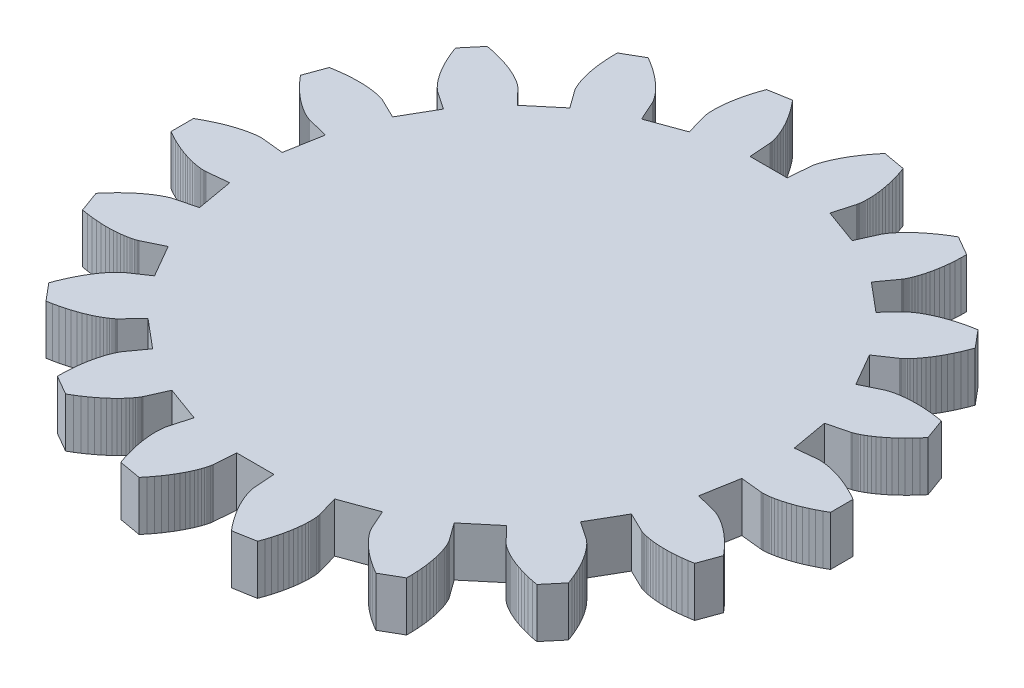
SolidWorks part; units mm, degrees
ref_plane "Front Plane" through (0, 0, 0) normal (0, 0, 1) x (1, 0, 0)
ref_plane "Top Plane" through (0, 0, 0) normal (0, 1, 0) x (1, 0, 0)
ref_plane "Right Plane" through (0, 0, 0) normal (1, 0, 0) x (0, 0, -1)
sketch "Sketch2" plane through (0, 0, 0) normal (0, 1, 0) x (1, 0, 0)
  line L0 (15.5186, 1.5911) -> (16.8263, 1.7252)
  line L1 (16.8263, 1.7252) -> (16.8356, 1.7259)
  line L2 (16.8356, 1.7259) -> (16.8635, 1.7273)
  line L3 (16.8635, 1.7273) -> (16.9101, 1.7282)
  line L4 (16.9101, 1.7282) -> (16.9754, 1.7272)
  line L5 (16.9754, 1.7272) -> (17.0592, 1.7232)
  line L6 (17.0592, 1.7232) -> (17.1615, 1.7149)
  line L7 (17.1615, 1.7149) -> (17.282, 1.7011)
  line L8 (17.282, 1.7011) -> (17.4203, 1.6805)
  line L9 (17.4203, 1.6805) -> (17.5763, 1.6521)
  line L10 (17.5763, 1.6521) -> (17.7495, 1.6145)
  line L11 (17.7495, 1.6145) -> (17.9394, 1.5667)
  line L12 (17.9394, 1.5667) -> (18.1456, 1.5074)
  line L13 (18.1456, 1.5074) -> (18.3674, 1.4356)
  line L14 (18.3674, 1.4356) -> (18.6042, 1.3501)
  line L15 (18.6042, 1.3501) -> (18.8555, 1.2499)
  line L16 (18.8555, 1.2499) -> (19.1203, 1.1339)
  line L17 (19.1203, 1.1339) -> (19.398, 1.0012)
  line L18 (19.398, 1.0012) -> (19.6876, 0.8507)
  line L19 (19.6876, 0.8507) -> (19.9884, 0.6815)
  line L20 (19.9884, 0.6815) -> (19.9884, -0.6815)
  line L21 (19.9884, -0.6815) -> (19.6876, -0.8507)
  line L22 (19.6876, -0.8507) -> (19.398, -1.0012)
  line L23 (19.398, -1.0012) -> (19.1203, -1.1339)
  line L24 (19.1203, -1.1339) -> (18.8555, -1.2499)
  line L25 (18.8555, -1.2499) -> (18.6042, -1.3501)
  line L26 (18.6042, -1.3501) -> (18.3674, -1.4356)
  line L27 (18.3674, -1.4356) -> (18.1456, -1.5074)
  line L28 (18.1456, -1.5074) -> (17.9394, -1.5667)
  line L29 (17.9394, -1.5667) -> (17.7495, -1.6145)
  line L30 (17.7495, -1.6145) -> (17.5763, -1.6521)
  line L31 (17.5763, -1.6521) -> (17.4203, -1.6805)
  line L32 (17.4203, -1.6805) -> (17.282, -1.7011)
  line L33 (17.282, -1.7011) -> (17.1615, -1.7149)
  line L34 (17.1615, -1.7149) -> (17.0592, -1.7232)
  line L35 (17.0592, -1.7232) -> (16.9754, -1.7272)
  line L36 (16.9754, -1.7272) -> (16.9101, -1.7282)
  line L37 (16.9101, -1.7282) -> (16.8635, -1.7273)
  line L38 (16.8635, -1.7273) -> (16.8356, -1.7259)
  line L39 (16.8356, -1.7259) -> (16.8263, -1.7252)
  line L40 (16.8263, -1.7252) -> (15.5186, -1.5911)
  line L41 (15.5186, -1.5911) -> (15.1269, -3.8126)
  line L42 (15.1269, -3.8126) -> (16.4016, -4.1338)
  line L43 (16.4016, -4.1338) -> (16.4105, -4.1363)
  line L44 (16.4105, -4.1363) -> (16.4373, -4.1445)
  line L45 (16.4373, -4.1445) -> (16.4814, -4.1597)
  line L46 (16.4814, -4.1597) -> (16.5424, -4.1829)
  line L47 (16.5424, -4.1829) -> (16.6198, -4.2154)
  line L48 (16.6198, -4.2154) -> (16.7131, -4.2581)
  line L49 (16.7131, -4.2581) -> (16.8215, -4.3123)
  line L50 (16.8215, -4.3123) -> (16.9445, -4.3789)
  line L51 (16.9445, -4.3789) -> (17.0814, -4.459)
  line L52 (17.0814, -4.459) -> (17.2313, -4.5535)
  line L53 (17.2313, -4.5535) -> (17.3934, -4.6634)
  line L54 (17.3934, -4.6634) -> (17.5668, -4.7896)
  line L55 (17.5668, -4.7896) -> (17.7507, -4.933)
  line L56 (17.7507, -4.933) -> (17.944, -5.0943)
  line L57 (17.944, -5.0943) -> (18.1458, -5.2744)
  line L58 (18.1458, -5.2744) -> (18.355, -5.474)
  line L59 (18.355, -5.474) -> (18.5705, -5.6937)
  line L60 (18.5705, -5.6937) -> (18.7913, -5.9342)
  line L61 (18.7913, -5.9342) -> (19.016, -6.196)
  line L62 (19.016, -6.196) -> (18.5499, -7.4769)
  line L63 (18.5499, -7.4769) -> (18.2094, -7.5329)
  line L64 (18.2094, -7.5329) -> (17.8857, -7.5753)
  line L65 (17.8857, -7.5753) -> (17.5794, -7.6051)
  line L66 (17.5794, -7.6051) -> (17.2908, -7.6235)
  line L67 (17.2908, -7.6235) -> (17.0205, -7.6317)
  line L68 (17.0205, -7.6317) -> (16.7687, -7.631)
  line L69 (16.7687, -7.631) -> (16.5357, -7.6226)
  line L70 (16.5357, -7.6226) -> (16.3217, -7.6078)
  line L71 (16.3217, -7.6078) -> (16.1269, -7.5878)
  line L72 (16.1269, -7.5878) -> (15.9513, -7.5639)
  line L73 (15.9513, -7.5639) -> (15.795, -7.5373)
  line L74 (15.795, -7.5373) -> (15.6579, -7.5093)
  line L75 (15.6579, -7.5093) -> (15.54, -7.481)
  line L76 (15.54, -7.481) -> (15.4411, -7.4539)
  line L77 (15.4411, -7.4539) -> (15.3609, -7.429)
  line L78 (15.3609, -7.429) -> (15.2993, -7.4075)
  line L79 (15.2993, -7.4075) -> (15.2557, -7.3908)
  line L80 (15.2557, -7.3908) -> (15.23, -7.3799)
  line L81 (15.23, -7.3799) -> (15.2215, -7.376)
  line L82 (15.2215, -7.376) -> (14.0386, -6.8028)
  line L83 (14.0386, -6.8028) -> (12.9107, -8.7563)
  line L84 (12.9107, -8.7563) -> (13.9986, -9.4942)
  line L85 (13.9986, -9.4942) -> (14.0062, -9.4996)
  line L86 (14.0062, -9.4996) -> (14.0285, -9.5164)
  line L87 (14.0285, -9.5164) -> (14.0647, -9.5458)
  line L88 (14.0647, -9.5458) -> (14.1141, -9.5885)
  line L89 (14.1141, -9.5885) -> (14.1758, -9.6454)
  line L90 (14.1758, -9.6454) -> (14.2488, -9.7175)
  line L91 (14.2488, -9.7175) -> (14.3322, -9.8055)
  line L92 (14.3322, -9.8055) -> (14.425, -9.9102)
  line L93 (14.425, -9.9102) -> (14.5262, -10.0323)
  line L94 (14.5262, -10.0323) -> (14.6347, -10.1723)
  line L95 (14.6347, -10.1723) -> (14.7494, -10.3311)
  line L96 (14.7494, -10.3311) -> (14.8692, -10.509)
  line L97 (14.8692, -10.509) -> (14.993, -10.7066)
  line L98 (14.993, -10.7066) -> (15.1195, -10.9243)
  line L99 (15.1195, -10.9243) -> (15.2475, -11.1626)
  line L100 (15.2475, -11.1626) -> (15.3759, -11.4217)
  line L101 (15.3759, -11.4217) -> (15.5032, -11.7018)
  line L102 (15.5032, -11.7018) -> (15.6284, -12.0033)
  line L103 (15.6284, -12.0033) -> (15.7501, -12.3262)
  line L104 (15.7501, -12.3262) -> (14.8739, -13.3704)
  line L105 (14.8739, -13.3704) -> (14.5348, -13.3066)
  line L106 (14.5348, -13.3066) -> (14.2162, -13.2357)
  line L107 (14.2162, -13.2357) -> (13.9181, -13.1589)
  line L108 (13.9181, -13.1589) -> (13.6407, -13.0775)
  line L109 (13.6407, -13.0775) -> (13.3838, -12.9928)
  line L110 (13.3838, -12.9928) -> (13.1475, -12.906)
  line L111 (13.1475, -12.906) -> (12.9314, -12.8185)
  line L112 (12.9314, -12.8185) -> (12.7353, -12.7314)
  line L113 (12.7353, -12.7314) -> (12.5591, -12.6459)
  line L114 (12.5591, -12.6459) -> (12.4023, -12.5634)
  line L115 (12.4023, -12.5634) -> (12.2645, -12.4849)
  line L116 (12.2645, -12.4849) -> (12.1453, -12.4117)
  line L117 (12.1453, -12.4117) -> (12.0442, -12.3449)
  line L118 (12.0442, -12.3449) -> (11.9605, -12.2855)
  line L119 (11.9605, -12.2855) -> (11.8937, -12.2347)
  line L120 (11.8937, -12.2347) -> (11.8431, -12.1935)
  line L121 (11.8431, -12.1935) -> (11.8079, -12.1629)
  line L122 (11.8079, -12.1629) -> (11.7874, -12.1438)
  line L123 (11.7874, -12.1438) -> (11.7808, -12.1373)
  line L124 (11.7808, -12.1373) -> (10.8652, -11.194)
  line L125 (10.8652, -11.194) -> (9.1373, -12.644)
  line L126 (9.1373, -12.644) -> (9.9072, -13.7094)
  line L127 (9.9072, -13.7094) -> (9.9125, -13.7171)
  line L128 (9.9125, -13.7171) -> (9.9277, -13.7406)
  line L129 (9.9277, -13.7406) -> (9.9517, -13.7805)
  line L130 (9.9517, -13.7805) -> (9.9835, -13.8375)
  line L131 (9.9835, -13.8375) -> (10.0219, -13.9122)
  line L132 (10.0219, -13.9122) -> (10.0659, -14.0049)
  line L133 (10.0659, -14.0049) -> (10.1141, -14.1161)
  line L134 (10.1141, -14.1161) -> (10.1656, -14.2462)
  line L135 (10.1656, -14.2462) -> (10.2189, -14.3955)
  line L136 (10.2189, -14.3955) -> (10.273, -14.5642)
  line L137 (10.273, -14.5642) -> (10.3265, -14.7526)
  line L138 (10.3265, -14.7526) -> (10.3782, -14.9608)
  line L139 (10.3782, -14.9608) -> (10.4269, -15.1888)
  line L140 (10.4269, -15.1888) -> (10.4713, -15.4367)
  line L141 (10.4713, -15.4367) -> (10.5102, -15.7044)
  line L142 (10.5102, -15.7044) -> (10.5421, -15.9917)
  line L143 (10.5421, -15.9917) -> (10.566, -16.2985)
  line L144 (10.566, -16.2985) -> (10.5805, -16.6246)
  line L145 (10.5805, -16.6246) -> (10.5844, -16.9697)
  line L146 (10.5844, -16.9697) -> (9.404, -17.6512)
  line L147 (9.404, -17.6512) -> (9.1071, -17.4753)
  line L148 (9.1071, -17.4753) -> (8.8319, -17.2997)
  line L149 (8.8319, -17.2997) -> (8.5781, -17.1256)
  line L150 (8.5781, -17.1256) -> (8.3453, -16.9542)
  line L151 (8.3453, -16.9542) -> (8.1329, -16.7868)
  line L152 (8.1329, -16.7868) -> (7.9404, -16.6244)
  line L153 (7.9404, -16.6244) -> (7.7673, -16.4682)
  line L154 (7.7673, -16.4682) -> (7.6129, -16.3193)
  line L155 (7.6129, -16.3193) -> (7.4765, -16.1788)
  line L156 (7.4765, -16.1788) -> (7.3574, -16.0476)
  line L157 (7.3574, -16.0476) -> (7.2548, -15.9267)
  line L158 (7.2548, -15.9267) -> (7.1678, -15.8171)
  line L159 (7.1678, -15.8171) -> (7.0956, -15.7197)
  line L160 (7.0956, -15.7197) -> (7.0373, -15.6353)
  line L161 (7.0373, -15.6353) -> (6.9919, -15.5647)
  line L162 (6.9919, -15.5647) -> (6.9584, -15.5087)
  line L163 (6.9584, -15.5087) -> (6.9358, -15.4679)
  line L164 (6.9358, -15.4679) -> (6.9231, -15.443)
  line L165 (6.9231, -15.443) -> (6.9191, -15.4345)
  line L166 (6.9191, -15.4345) -> (6.3814, -14.2351)
  line L167 (6.3814, -14.2351) -> (4.2617, -15.0066)
  line L168 (4.2617, -15.0066) -> (4.6208, -16.2711)
  line L169 (4.6208, -16.2711) -> (4.6231, -16.2801)
  line L170 (4.6231, -16.2801) -> (4.6294, -16.3074)
  line L171 (4.6294, -16.3074) -> (4.6383, -16.3531)
  line L172 (4.6383, -16.3531) -> (4.6487, -16.4176)
  line L173 (4.6487, -16.4176) -> (4.6593, -16.5008)
  line L174 (4.6593, -16.5008) -> (4.6689, -16.603)
  line L175 (4.6689, -16.603) -> (4.6762, -16.724)
  line L176 (4.6762, -16.724) -> (4.68, -16.8639)
  line L177 (4.68, -16.8639) -> (4.6791, -17.0224)
  line L178 (4.6791, -17.0224) -> (4.6722, -17.1995)
  line L179 (4.6722, -17.1995) -> (4.658, -17.3948)
  line L180 (4.658, -17.3948) -> (4.6354, -17.6081)
  line L181 (4.6354, -17.6081) -> (4.6032, -17.8391)
  line L182 (4.6032, -17.8391) -> (4.5602, -18.0872)
  line L183 (4.5602, -18.0872) -> (4.5051, -18.352)
  line L184 (4.5051, -18.352) -> (4.4369, -18.6329)
  line L185 (4.4369, -18.6329) -> (4.3544, -18.9294)
  line L186 (4.3544, -18.9294) -> (4.2565, -19.2408)
  line L187 (4.2565, -19.2408) -> (4.1421, -19.5664)
  line L188 (4.1421, -19.5664) -> (2.7998, -19.8031)
  line L189 (2.7998, -19.8031) -> (2.581, -19.5363)
  line L190 (2.581, -19.5363) -> (2.3825, -19.2771)
  line L191 (2.3825, -19.2771) -> (2.2035, -19.0267)
  line L192 (2.2035, -19.0267) -> (2.0433, -18.786)
  line L193 (2.0433, -18.786) -> (1.901, -18.556)
  line L194 (1.901, -18.556) -> (1.7757, -18.3376)
  line L195 (1.7757, -18.3376) -> (1.6664, -18.1316)
  line L196 (1.6664, -18.1316) -> (1.5723, -17.9389)
  line L197 (1.5723, -17.9389) -> (1.4922, -17.7602)
  line L198 (1.4922, -17.7602) -> (1.4251, -17.5962)
  line L199 (1.4251, -17.5962) -> (1.37, -17.4475)
  line L200 (1.37, -17.4475) -> (1.3258, -17.3148)
  line L201 (1.3258, -17.3148) -> (1.2912, -17.1986)
  line L202 (1.2912, -17.1986) -> (1.2653, -17.0993)
  line L203 (1.2653, -17.0993) -> (1.2468, -17.0174)
  line L204 (1.2468, -17.0174) -> (1.2345, -16.9533)
  line L205 (1.2345, -16.9533) -> (1.2272, -16.9073)
  line L206 (1.2272, -16.9073) -> (1.2238, -16.8795)
  line L207 (1.2238, -16.8795) -> (1.2229, -16.8702)
  line L208 (1.2229, -16.8702) -> (1.1279, -15.5592)
  line L209 (1.1279, -15.5592) -> (-1.1279, -15.5592)
  line L210 (-1.1279, -15.5592) -> (-1.2229, -16.8702)
  line L211 (-1.2229, -16.8702) -> (-1.2238, -16.8795)
  line L212 (-1.2238, -16.8795) -> (-1.2272, -16.9073)
  line L213 (-1.2272, -16.9073) -> (-1.2345, -16.9533)
  line L214 (-1.2345, -16.9533) -> (-1.2468, -17.0174)
  line L215 (-1.2468, -17.0174) -> (-1.2653, -17.0993)
  line L216 (-1.2653, -17.0993) -> (-1.2912, -17.1986)
  line L217 (-1.2912, -17.1986) -> (-1.3258, -17.3148)
  line L218 (-1.3258, -17.3148) -> (-1.37, -17.4475)
  line L219 (-1.37, -17.4475) -> (-1.4251, -17.5962)
  line L220 (-1.4251, -17.5962) -> (-1.4922, -17.7602)
  line L221 (-1.4922, -17.7602) -> (-1.5723, -17.9389)
  line L222 (-1.5723, -17.9389) -> (-1.6664, -18.1316)
  line L223 (-1.6664, -18.1316) -> (-1.7757, -18.3376)
  line L224 (-1.7757, -18.3376) -> (-1.901, -18.556)
  line L225 (-1.901, -18.556) -> (-2.0433, -18.786)
  line L226 (-2.0433, -18.786) -> (-2.2035, -19.0267)
  line L227 (-2.2035, -19.0267) -> (-2.3825, -19.2771)
  line L228 (-2.3825, -19.2771) -> (-2.581, -19.5363)
  line L229 (-2.581, -19.5363) -> (-2.7998, -19.8031)
  line L230 (-2.7998, -19.8031) -> (-4.1421, -19.5664)
  line L231 (-4.1421, -19.5664) -> (-4.2565, -19.2408)
  line L232 (-4.2565, -19.2408) -> (-4.3544, -18.9294)
  line L233 (-4.3544, -18.9294) -> (-4.4369, -18.6329)
  line L234 (-4.4369, -18.6329) -> (-4.5051, -18.352)
  line L235 (-4.5051, -18.352) -> (-4.5602, -18.0872)
  line L236 (-4.5602, -18.0872) -> (-4.6032, -17.8391)
  line L237 (-4.6032, -17.8391) -> (-4.6354, -17.6081)
  line L238 (-4.6354, -17.6081) -> (-4.658, -17.3948)
  line L239 (-4.658, -17.3948) -> (-4.6722, -17.1995)
  line L240 (-4.6722, -17.1995) -> (-4.6791, -17.0224)
  line L241 (-4.6791, -17.0224) -> (-4.68, -16.8639)
  line L242 (-4.68, -16.8639) -> (-4.6762, -16.724)
  line L243 (-4.6762, -16.724) -> (-4.6689, -16.603)
  line L244 (-4.6689, -16.603) -> (-4.6593, -16.5008)
  line L245 (-4.6593, -16.5008) -> (-4.6487, -16.4176)
  line L246 (-4.6487, -16.4176) -> (-4.6383, -16.3531)
  line L247 (-4.6383, -16.3531) -> (-4.6294, -16.3074)
  line L248 (-4.6294, -16.3074) -> (-4.6231, -16.2801)
  line L249 (-4.6231, -16.2801) -> (-4.6208, -16.2711)
  line L250 (-4.6208, -16.2711) -> (-4.2617, -15.0066)
  line L251 (-4.2617, -15.0066) -> (-6.3814, -14.2351)
  line L252 (-6.3814, -14.2351) -> (-6.9191, -15.4345)
  line L253 (-6.9191, -15.4345) -> (-6.9231, -15.443)
  line L254 (-6.9231, -15.443) -> (-6.9358, -15.4679)
  line L255 (-6.9358, -15.4679) -> (-6.9584, -15.5087)
  line L256 (-6.9584, -15.5087) -> (-6.9919, -15.5647)
  line L257 (-6.9919, -15.5647) -> (-7.0373, -15.6353)
  line L258 (-7.0373, -15.6353) -> (-7.0956, -15.7197)
  line L259 (-7.0956, -15.7197) -> (-7.1678, -15.8171)
  line L260 (-7.1678, -15.8171) -> (-7.2548, -15.9267)
  line L261 (-7.2548, -15.9267) -> (-7.3574, -16.0476)
  line L262 (-7.3574, -16.0476) -> (-7.4765, -16.1788)
  line L263 (-7.4765, -16.1788) -> (-7.6129, -16.3193)
  line L264 (-7.6129, -16.3193) -> (-7.7673, -16.4682)
  line L265 (-7.7673, -16.4682) -> (-7.9404, -16.6244)
  line L266 (-7.9404, -16.6244) -> (-8.1329, -16.7868)
  line L267 (-8.1329, -16.7868) -> (-8.3453, -16.9542)
  line L268 (-8.3453, -16.9542) -> (-8.5781, -17.1256)
  line L269 (-8.5781, -17.1256) -> (-8.8319, -17.2997)
  line L270 (-8.8319, -17.2997) -> (-9.1071, -17.4753)
  line L271 (-9.1071, -17.4753) -> (-9.404, -17.6512)
  line L272 (-9.404, -17.6512) -> (-10.5844, -16.9697)
  line L273 (-10.5844, -16.9697) -> (-10.5805, -16.6246)
  line L274 (-10.5805, -16.6246) -> (-10.566, -16.2985)
  line L275 (-10.566, -16.2985) -> (-10.5421, -15.9917)
  line L276 (-10.5421, -15.9917) -> (-10.5102, -15.7044)
  line L277 (-10.5102, -15.7044) -> (-10.4713, -15.4367)
  line L278 (-10.4713, -15.4367) -> (-10.4269, -15.1888)
  line L279 (-10.4269, -15.1888) -> (-10.3782, -14.9608)
  line L280 (-10.3782, -14.9608) -> (-10.3265, -14.7526)
  line L281 (-10.3265, -14.7526) -> (-10.273, -14.5642)
  line L282 (-10.273, -14.5642) -> (-10.2189, -14.3955)
  line L283 (-10.2189, -14.3955) -> (-10.1656, -14.2462)
  line L284 (-10.1656, -14.2462) -> (-10.1141, -14.1161)
  line L285 (-10.1141, -14.1161) -> (-10.0659, -14.0049)
  line L286 (-10.0659, -14.0049) -> (-10.0219, -13.9122)
  line L287 (-10.0219, -13.9122) -> (-9.9835, -13.8375)
  line L288 (-9.9835, -13.8375) -> (-9.9517, -13.7805)
  line L289 (-9.9517, -13.7805) -> (-9.9277, -13.7406)
  line L290 (-9.9277, -13.7406) -> (-9.9125, -13.7171)
  line L291 (-9.9125, -13.7171) -> (-9.9072, -13.7094)
  line L292 (-9.9072, -13.7094) -> (-9.1373, -12.644)
  line L293 (-9.1373, -12.644) -> (-10.8652, -11.194)
  line L294 (-10.8652, -11.194) -> (-11.7808, -12.1373)
  line L295 (-11.7808, -12.1373) -> (-11.7874, -12.1438)
  line L296 (-11.7874, -12.1438) -> (-11.8079, -12.1629)
  line L297 (-11.8079, -12.1629) -> (-11.8431, -12.1935)
  line L298 (-11.8431, -12.1935) -> (-11.8937, -12.2347)
  line L299 (-11.8937, -12.2347) -> (-11.9605, -12.2855)
  line L300 (-11.9605, -12.2855) -> (-12.0442, -12.3449)
  line L301 (-12.0442, -12.3449) -> (-12.1453, -12.4117)
  line L302 (-12.1453, -12.4117) -> (-12.2645, -12.4849)
  line L303 (-12.2645, -12.4849) -> (-12.4023, -12.5634)
  line L304 (-12.4023, -12.5634) -> (-12.5591, -12.6459)
  line L305 (-12.5591, -12.6459) -> (-12.7353, -12.7314)
  line L306 (-12.7353, -12.7314) -> (-12.9314, -12.8185)
  line L307 (-12.9314, -12.8185) -> (-13.1475, -12.906)
  line L308 (-13.1475, -12.906) -> (-13.3838, -12.9928)
  line L309 (-13.3838, -12.9928) -> (-13.6407, -13.0775)
  line L310 (-13.6407, -13.0775) -> (-13.9181, -13.1589)
  line L311 (-13.9181, -13.1589) -> (-14.2162, -13.2357)
  line L312 (-14.2162, -13.2357) -> (-14.5348, -13.3066)
  line L313 (-14.5348, -13.3066) -> (-14.8739, -13.3704)
  line L314 (-14.8739, -13.3704) -> (-15.7501, -12.3262)
  line L315 (-15.7501, -12.3262) -> (-15.6284, -12.0033)
  line L316 (-15.6284, -12.0033) -> (-15.5032, -11.7018)
  line L317 (-15.5032, -11.7018) -> (-15.3759, -11.4217)
  line L318 (-15.3759, -11.4217) -> (-15.2475, -11.1626)
  line L319 (-15.2475, -11.1626) -> (-15.1195, -10.9243)
  line L320 (-15.1195, -10.9243) -> (-14.993, -10.7066)
  line L321 (-14.993, -10.7066) -> (-14.8692, -10.509)
  line L322 (-14.8692, -10.509) -> (-14.7494, -10.3311)
  line L323 (-14.7494, -10.3311) -> (-14.6347, -10.1723)
  line L324 (-14.6347, -10.1723) -> (-14.5262, -10.0323)
  line L325 (-14.5262, -10.0323) -> (-14.425, -9.9102)
  line L326 (-14.425, -9.9102) -> (-14.3322, -9.8055)
  line L327 (-14.3322, -9.8055) -> (-14.2488, -9.7175)
  line L328 (-14.2488, -9.7175) -> (-14.1758, -9.6454)
  line L329 (-14.1758, -9.6454) -> (-14.1141, -9.5885)
  line L330 (-14.1141, -9.5885) -> (-14.0647, -9.5458)
  line L331 (-14.0647, -9.5458) -> (-14.0285, -9.5164)
  line L332 (-14.0285, -9.5164) -> (-14.0062, -9.4996)
  line L333 (-14.0062, -9.4996) -> (-13.9986, -9.4942)
  line L334 (-13.9986, -9.4942) -> (-12.9107, -8.7563)
  line L335 (-12.9107, -8.7563) -> (-14.0386, -6.8028)
  line L336 (-14.0386, -6.8028) -> (-15.2215, -7.376)
  line L337 (-15.2215, -7.376) -> (-15.23, -7.3799)
  line L338 (-15.23, -7.3799) -> (-15.2557, -7.3908)
  line L339 (-15.2557, -7.3908) -> (-15.2993, -7.4075)
  line L340 (-15.2993, -7.4075) -> (-15.3609, -7.429)
  line L341 (-15.3609, -7.429) -> (-15.4411, -7.4539)
  line L342 (-15.4411, -7.4539) -> (-15.54, -7.481)
  line L343 (-15.54, -7.481) -> (-15.6579, -7.5093)
  line L344 (-15.6579, -7.5093) -> (-15.795, -7.5373)
  line L345 (-15.795, -7.5373) -> (-15.9513, -7.5639)
  line L346 (-15.9513, -7.5639) -> (-16.1269, -7.5878)
  line L347 (-16.1269, -7.5878) -> (-16.3217, -7.6078)
  line L348 (-16.3217, -7.6078) -> (-16.5357, -7.6226)
  line L349 (-16.5357, -7.6226) -> (-16.7687, -7.631)
  line L350 (-16.7687, -7.631) -> (-17.0205, -7.6317)
  line L351 (-17.0205, -7.6317) -> (-17.2908, -7.6235)
  line L352 (-17.2908, -7.6235) -> (-17.5794, -7.6051)
  line L353 (-17.5794, -7.6051) -> (-17.8857, -7.5753)
  line L354 (-17.8857, -7.5753) -> (-18.2094, -7.5329)
  line L355 (-18.2094, -7.5329) -> (-18.5499, -7.4769)
  line L356 (-18.5499, -7.4769) -> (-19.016, -6.196)
  line L357 (-19.016, -6.196) -> (-18.7913, -5.9342)
  line L358 (-18.7913, -5.9342) -> (-18.5705, -5.6937)
  line L359 (-18.5705, -5.6937) -> (-18.355, -5.474)
  line L360 (-18.355, -5.474) -> (-18.1458, -5.2744)
  line L361 (-18.1458, -5.2744) -> (-17.944, -5.0943)
  line L362 (-17.944, -5.0943) -> (-17.7507, -4.933)
  line L363 (-17.7507, -4.933) -> (-17.5668, -4.7896)
  line L364 (-17.5668, -4.7896) -> (-17.3934, -4.6634)
  line L365 (-17.3934, -4.6634) -> (-17.2313, -4.5535)
  line L366 (-17.2313, -4.5535) -> (-17.0814, -4.459)
  line L367 (-17.0814, -4.459) -> (-16.9445, -4.3789)
  line L368 (-16.9445, -4.3789) -> (-16.8215, -4.3123)
  line L369 (-16.8215, -4.3123) -> (-16.7131, -4.2581)
  line L370 (-16.7131, -4.2581) -> (-16.6198, -4.2154)
  line L371 (-16.6198, -4.2154) -> (-16.5424, -4.1829)
  line L372 (-16.5424, -4.1829) -> (-16.4814, -4.1597)
  line L373 (-16.4814, -4.1597) -> (-16.4373, -4.1445)
  line L374 (-16.4373, -4.1445) -> (-16.4105, -4.1363)
  line L375 (-16.4105, -4.1363) -> (-16.4016, -4.1338)
  line L376 (-16.4016, -4.1338) -> (-15.1269, -3.8126)
  line L377 (-15.1269, -3.8126) -> (-15.5186, -1.5911)
  line L378 (-15.5186, -1.5911) -> (-16.8263, -1.7252)
  line L379 (-16.8263, -1.7252) -> (-16.8356, -1.7259)
  line L380 (-16.8356, -1.7259) -> (-16.8635, -1.7273)
  line L381 (-16.8635, -1.7273) -> (-16.9101, -1.7282)
  line L382 (-16.9101, -1.7282) -> (-16.9754, -1.7272)
  line L383 (-16.9754, -1.7272) -> (-17.0592, -1.7232)
  line L384 (-17.0592, -1.7232) -> (-17.1615, -1.7149)
  line L385 (-17.1615, -1.7149) -> (-17.282, -1.7011)
  line L386 (-17.282, -1.7011) -> (-17.4203, -1.6805)
  line L387 (-17.4203, -1.6805) -> (-17.5763, -1.6521)
  line L388 (-17.5763, -1.6521) -> (-17.7495, -1.6145)
  line L389 (-17.7495, -1.6145) -> (-17.9394, -1.5667)
  line L390 (-17.9394, -1.5667) -> (-18.1456, -1.5074)
  line L391 (-18.1456, -1.5074) -> (-18.3674, -1.4356)
  line L392 (-18.3674, -1.4356) -> (-18.6042, -1.3501)
  line L393 (-18.6042, -1.3501) -> (-18.8555, -1.2499)
  line L394 (-18.8555, -1.2499) -> (-19.1203, -1.1339)
  line L395 (-19.1203, -1.1339) -> (-19.398, -1.0012)
  line L396 (-19.398, -1.0012) -> (-19.6876, -0.8507)
  line L397 (-19.6876, -0.8507) -> (-19.9884, -0.6815)
  line L398 (-19.9884, -0.6815) -> (-19.9884, 0.6815)
  line L399 (-19.9884, 0.6815) -> (-19.6876, 0.8507)
  line L400 (-19.6876, 0.8507) -> (-19.398, 1.0012)
  line L401 (-19.398, 1.0012) -> (-19.1203, 1.1339)
  line L402 (-19.1203, 1.1339) -> (-18.8555, 1.2499)
  line L403 (-18.8555, 1.2499) -> (-18.6042, 1.3501)
  line L404 (-18.6042, 1.3501) -> (-18.3674, 1.4356)
  line L405 (-18.3674, 1.4356) -> (-18.1456, 1.5074)
  line L406 (-18.1456, 1.5074) -> (-17.9394, 1.5667)
  line L407 (-17.9394, 1.5667) -> (-17.7495, 1.6145)
  line L408 (-17.7495, 1.6145) -> (-17.5763, 1.6521)
  line L409 (-17.5763, 1.6521) -> (-17.4203, 1.6805)
  line L410 (-17.4203, 1.6805) -> (-17.282, 1.7011)
  line L411 (-17.282, 1.7011) -> (-17.1615, 1.7149)
  line L412 (-17.1615, 1.7149) -> (-17.0592, 1.7232)
  line L413 (-17.0592, 1.7232) -> (-16.9754, 1.7272)
  line L414 (-16.9754, 1.7272) -> (-16.9101, 1.7282)
  line L415 (-16.9101, 1.7282) -> (-16.8635, 1.7273)
  line L416 (-16.8635, 1.7273) -> (-16.8356, 1.7259)
  line L417 (-16.8356, 1.7259) -> (-16.8263, 1.7252)
  line L418 (-16.8263, 1.7252) -> (-15.5186, 1.5911)
  line L419 (-15.5186, 1.5911) -> (-15.1269, 3.8126)
  line L420 (-15.1269, 3.8126) -> (-16.4016, 4.1338)
  line L421 (-16.4016, 4.1338) -> (-16.4105, 4.1363)
  line L422 (-16.4105, 4.1363) -> (-16.4373, 4.1445)
  line L423 (-16.4373, 4.1445) -> (-16.4814, 4.1597)
  line L424 (-16.4814, 4.1597) -> (-16.5424, 4.1829)
  line L425 (-16.5424, 4.1829) -> (-16.6198, 4.2154)
  line L426 (-16.6198, 4.2154) -> (-16.7131, 4.2581)
  line L427 (-16.7131, 4.2581) -> (-16.8215, 4.3123)
  line L428 (-16.8215, 4.3123) -> (-16.9445, 4.3789)
  line L429 (-16.9445, 4.3789) -> (-17.0814, 4.459)
  line L430 (-17.0814, 4.459) -> (-17.2313, 4.5535)
  line L431 (-17.2313, 4.5535) -> (-17.3934, 4.6634)
  line L432 (-17.3934, 4.6634) -> (-17.5668, 4.7896)
  line L433 (-17.5668, 4.7896) -> (-17.7507, 4.933)
  line L434 (-17.7507, 4.933) -> (-17.944, 5.0943)
  line L435 (-17.944, 5.0943) -> (-18.1458, 5.2744)
  line L436 (-18.1458, 5.2744) -> (-18.355, 5.474)
  line L437 (-18.355, 5.474) -> (-18.5705, 5.6937)
  line L438 (-18.5705, 5.6937) -> (-18.7913, 5.9342)
  line L439 (-18.7913, 5.9342) -> (-19.016, 6.196)
  line L440 (-19.016, 6.196) -> (-18.5499, 7.4769)
  line L441 (-18.5499, 7.4769) -> (-18.2094, 7.5329)
  line L442 (-18.2094, 7.5329) -> (-17.8857, 7.5753)
  line L443 (-17.8857, 7.5753) -> (-17.5794, 7.6051)
  line L444 (-17.5794, 7.6051) -> (-17.2908, 7.6235)
  line L445 (-17.2908, 7.6235) -> (-17.0205, 7.6317)
  line L446 (-17.0205, 7.6317) -> (-16.7687, 7.631)
  line L447 (-16.7687, 7.631) -> (-16.5357, 7.6226)
  line L448 (-16.5357, 7.6226) -> (-16.3217, 7.6078)
  line L449 (-16.3217, 7.6078) -> (-16.1269, 7.5878)
  line L450 (-16.1269, 7.5878) -> (-15.9513, 7.5639)
  line L451 (-15.9513, 7.5639) -> (-15.795, 7.5373)
  line L452 (-15.795, 7.5373) -> (-15.6579, 7.5093)
  line L453 (-15.6579, 7.5093) -> (-15.54, 7.481)
  line L454 (-15.54, 7.481) -> (-15.4411, 7.4539)
  line L455 (-15.4411, 7.4539) -> (-15.3609, 7.429)
  line L456 (-15.3609, 7.429) -> (-15.2993, 7.4075)
  line L457 (-15.2993, 7.4075) -> (-15.2557, 7.3908)
  line L458 (-15.2557, 7.3908) -> (-15.23, 7.3799)
  line L459 (-15.23, 7.3799) -> (-15.2215, 7.376)
  line L460 (-15.2215, 7.376) -> (-14.0386, 6.8028)
  line L461 (-14.0386, 6.8028) -> (-12.9107, 8.7563)
  line L462 (-12.9107, 8.7563) -> (-13.9986, 9.4942)
  line L463 (-13.9986, 9.4942) -> (-14.0062, 9.4996)
  line L464 (-14.0062, 9.4996) -> (-14.0285, 9.5164)
  line L465 (-14.0285, 9.5164) -> (-14.0647, 9.5458)
  line L466 (-14.0647, 9.5458) -> (-14.1141, 9.5885)
  line L467 (-14.1141, 9.5885) -> (-14.1758, 9.6454)
  line L468 (-14.1758, 9.6454) -> (-14.2488, 9.7175)
  line L469 (-14.2488, 9.7175) -> (-14.3322, 9.8055)
  line L470 (-14.3322, 9.8055) -> (-14.425, 9.9102)
  line L471 (-14.425, 9.9102) -> (-14.5262, 10.0323)
  line L472 (-14.5262, 10.0323) -> (-14.6347, 10.1723)
  line L473 (-14.6347, 10.1723) -> (-14.7494, 10.3311)
  line L474 (-14.7494, 10.3311) -> (-14.8692, 10.509)
  line L475 (-14.8692, 10.509) -> (-14.993, 10.7066)
  line L476 (-14.993, 10.7066) -> (-15.1195, 10.9243)
  line L477 (-15.1195, 10.9243) -> (-15.2475, 11.1626)
  line L478 (-15.2475, 11.1626) -> (-15.3759, 11.4217)
  line L479 (-15.3759, 11.4217) -> (-15.5032, 11.7018)
  line L480 (-15.5032, 11.7018) -> (-15.6284, 12.0033)
  line L481 (-15.6284, 12.0033) -> (-15.7501, 12.3262)
  line L482 (-15.7501, 12.3262) -> (-14.8739, 13.3704)
  line L483 (-14.8739, 13.3704) -> (-14.5348, 13.3066)
  line L484 (-14.5348, 13.3066) -> (-14.2162, 13.2357)
  line L485 (-14.2162, 13.2357) -> (-13.9181, 13.1589)
  line L486 (-13.9181, 13.1589) -> (-13.6407, 13.0775)
  line L487 (-13.6407, 13.0775) -> (-13.3838, 12.9928)
  line L488 (-13.3838, 12.9928) -> (-13.1475, 12.906)
  line L489 (-13.1475, 12.906) -> (-12.9314, 12.8185)
  line L490 (-12.9314, 12.8185) -> (-12.7353, 12.7314)
  line L491 (-12.7353, 12.7314) -> (-12.5591, 12.6459)
  line L492 (-12.5591, 12.6459) -> (-12.4023, 12.5634)
  line L493 (-12.4023, 12.5634) -> (-12.2645, 12.4849)
  line L494 (-12.2645, 12.4849) -> (-12.1453, 12.4117)
  line L495 (-12.1453, 12.4117) -> (-12.0442, 12.3449)
  line L496 (-12.0442, 12.3449) -> (-11.9605, 12.2855)
  line L497 (-11.9605, 12.2855) -> (-11.8937, 12.2347)
  line L498 (-11.8937, 12.2347) -> (-11.8431, 12.1935)
  line L499 (-11.8431, 12.1935) -> (-11.8079, 12.1629)
  line L500 (-11.8079, 12.1629) -> (-11.7874, 12.1438)
  line L501 (-11.7874, 12.1438) -> (-11.7808, 12.1373)
  line L502 (-11.7808, 12.1373) -> (-10.8652, 11.194)
  line L503 (-10.8652, 11.194) -> (-9.1373, 12.644)
  line L504 (-9.1373, 12.644) -> (-9.9072, 13.7094)
  line L505 (-9.9072, 13.7094) -> (-9.9125, 13.7171)
  line L506 (-9.9125, 13.7171) -> (-9.9277, 13.7406)
  line L507 (-9.9277, 13.7406) -> (-9.9517, 13.7805)
  line L508 (-9.9517, 13.7805) -> (-9.9835, 13.8375)
  line L509 (-9.9835, 13.8375) -> (-10.0219, 13.9122)
  line L510 (-10.0219, 13.9122) -> (-10.0659, 14.0049)
  line L511 (-10.0659, 14.0049) -> (-10.1141, 14.1161)
  line L512 (-10.1141, 14.1161) -> (-10.1656, 14.2462)
  line L513 (-10.1656, 14.2462) -> (-10.2189, 14.3955)
  line L514 (-10.2189, 14.3955) -> (-10.273, 14.5642)
  line L515 (-10.273, 14.5642) -> (-10.3265, 14.7526)
  line L516 (-10.3265, 14.7526) -> (-10.3782, 14.9608)
  line L517 (-10.3782, 14.9608) -> (-10.4269, 15.1888)
  line L518 (-10.4269, 15.1888) -> (-10.4713, 15.4367)
  line L519 (-10.4713, 15.4367) -> (-10.5102, 15.7044)
  line L520 (-10.5102, 15.7044) -> (-10.5421, 15.9917)
  line L521 (-10.5421, 15.9917) -> (-10.566, 16.2985)
  line L522 (-10.566, 16.2985) -> (-10.5805, 16.6246)
  line L523 (-10.5805, 16.6246) -> (-10.5844, 16.9697)
  line L524 (-10.5844, 16.9697) -> (-9.404, 17.6512)
  line L525 (-9.404, 17.6512) -> (-9.1071, 17.4753)
  line L526 (-9.1071, 17.4753) -> (-8.8319, 17.2997)
  line L527 (-8.8319, 17.2997) -> (-8.5781, 17.1256)
  line L528 (-8.5781, 17.1256) -> (-8.3453, 16.9542)
  line L529 (-8.3453, 16.9542) -> (-8.1329, 16.7868)
  line L530 (-8.1329, 16.7868) -> (-7.9404, 16.6244)
  line L531 (-7.9404, 16.6244) -> (-7.7673, 16.4682)
  line L532 (-7.7673, 16.4682) -> (-7.6129, 16.3193)
  line L533 (-7.6129, 16.3193) -> (-7.4765, 16.1788)
  line L534 (-7.4765, 16.1788) -> (-7.3574, 16.0476)
  line L535 (-7.3574, 16.0476) -> (-7.2548, 15.9267)
  line L536 (-7.2548, 15.9267) -> (-7.1678, 15.8171)
  line L537 (-7.1678, 15.8171) -> (-7.0956, 15.7197)
  line L538 (-7.0956, 15.7197) -> (-7.0373, 15.6353)
  line L539 (-7.0373, 15.6353) -> (-6.9919, 15.5647)
  line L540 (-6.9919, 15.5647) -> (-6.9584, 15.5087)
  line L541 (-6.9584, 15.5087) -> (-6.9358, 15.4679)
  line L542 (-6.9358, 15.4679) -> (-6.9231, 15.443)
  line L543 (-6.9231, 15.443) -> (-6.9191, 15.4345)
  line L544 (-6.9191, 15.4345) -> (-6.3814, 14.2351)
  line L545 (-6.3814, 14.2351) -> (-4.2617, 15.0066)
  line L546 (-4.2617, 15.0066) -> (-4.6208, 16.2711)
  line L547 (-4.6208, 16.2711) -> (-4.6231, 16.2801)
  line L548 (-4.6231, 16.2801) -> (-4.6294, 16.3074)
  line L549 (-4.6294, 16.3074) -> (-4.6383, 16.3531)
  line L550 (-4.6383, 16.3531) -> (-4.6487, 16.4176)
  line L551 (-4.6487, 16.4176) -> (-4.6593, 16.5008)
  line L552 (-4.6593, 16.5008) -> (-4.6689, 16.603)
  line L553 (-4.6689, 16.603) -> (-4.6762, 16.724)
  line L554 (-4.6762, 16.724) -> (-4.68, 16.8639)
  line L555 (-4.68, 16.8639) -> (-4.6791, 17.0224)
  line L556 (-4.6791, 17.0224) -> (-4.6722, 17.1995)
  line L557 (-4.6722, 17.1995) -> (-4.658, 17.3948)
  line L558 (-4.658, 17.3948) -> (-4.6354, 17.6081)
  line L559 (-4.6354, 17.6081) -> (-4.6032, 17.8391)
  line L560 (-4.6032, 17.8391) -> (-4.5602, 18.0872)
  line L561 (-4.5602, 18.0872) -> (-4.5051, 18.352)
  line L562 (-4.5051, 18.352) -> (-4.4369, 18.6329)
  line L563 (-4.4369, 18.6329) -> (-4.3544, 18.9294)
  line L564 (-4.3544, 18.9294) -> (-4.2565, 19.2408)
  line L565 (-4.2565, 19.2408) -> (-4.1421, 19.5664)
  line L566 (-4.1421, 19.5664) -> (-2.7998, 19.8031)
  line L567 (-2.7998, 19.8031) -> (-2.581, 19.5363)
  line L568 (-2.581, 19.5363) -> (-2.3825, 19.2771)
  line L569 (-2.3825, 19.2771) -> (-2.2035, 19.0267)
  line L570 (-2.2035, 19.0267) -> (-2.0433, 18.786)
  line L571 (-2.0433, 18.786) -> (-1.901, 18.556)
  line L572 (-1.901, 18.556) -> (-1.7757, 18.3376)
  line L573 (-1.7757, 18.3376) -> (-1.6664, 18.1316)
  line L574 (-1.6664, 18.1316) -> (-1.5723, 17.9389)
  line L575 (-1.5723, 17.9389) -> (-1.4922, 17.7602)
  line L576 (-1.4922, 17.7602) -> (-1.4251, 17.5962)
  line L577 (-1.4251, 17.5962) -> (-1.37, 17.4475)
  line L578 (-1.37, 17.4475) -> (-1.3258, 17.3148)
  line L579 (-1.3258, 17.3148) -> (-1.2912, 17.1986)
  line L580 (-1.2912, 17.1986) -> (-1.2653, 17.0993)
  line L581 (-1.2653, 17.0993) -> (-1.2468, 17.0174)
  line L582 (-1.2468, 17.0174) -> (-1.2345, 16.9533)
  line L583 (-1.2345, 16.9533) -> (-1.2272, 16.9073)
  line L584 (-1.2272, 16.9073) -> (-1.2238, 16.8795)
  line L585 (-1.2238, 16.8795) -> (-1.2229, 16.8702)
  line L586 (-1.2229, 16.8702) -> (-1.1279, 15.5592)
  line L587 (-1.1279, 15.5592) -> (1.1279, 15.5592)
  line L588 (1.1279, 15.5592) -> (1.2229, 16.8702)
  line L589 (1.2229, 16.8702) -> (1.2238, 16.8795)
  line L590 (1.2238, 16.8795) -> (1.2272, 16.9073)
  line L591 (1.2272, 16.9073) -> (1.2345, 16.9533)
  line L592 (1.2345, 16.9533) -> (1.2468, 17.0174)
  line L593 (1.2468, 17.0174) -> (1.2653, 17.0993)
  line L594 (1.2653, 17.0993) -> (1.2912, 17.1986)
  line L595 (1.2912, 17.1986) -> (1.3258, 17.3148)
  line L596 (1.3258, 17.3148) -> (1.37, 17.4475)
  line L597 (1.37, 17.4475) -> (1.4251, 17.5962)
  line L598 (1.4251, 17.5962) -> (1.4922, 17.7602)
  line L599 (1.4922, 17.7602) -> (1.5723, 17.9389)
  line L600 (1.5723, 17.9389) -> (1.6664, 18.1316)
  line L601 (1.6664, 18.1316) -> (1.7757, 18.3376)
  line L602 (1.7757, 18.3376) -> (1.901, 18.556)
  line L603 (1.901, 18.556) -> (2.0433, 18.786)
  line L604 (2.0433, 18.786) -> (2.2035, 19.0267)
  line L605 (2.2035, 19.0267) -> (2.3825, 19.2771)
  line L606 (2.3825, 19.2771) -> (2.581, 19.5363)
  line L607 (2.581, 19.5363) -> (2.7998, 19.8031)
  line L608 (2.7998, 19.8031) -> (4.1421, 19.5664)
  line L609 (4.1421, 19.5664) -> (4.2565, 19.2408)
  line L610 (4.2565, 19.2408) -> (4.3544, 18.9294)
  line L611 (4.3544, 18.9294) -> (4.4369, 18.6329)
  line L612 (4.4369, 18.6329) -> (4.5051, 18.352)
  line L613 (4.5051, 18.352) -> (4.5602, 18.0872)
  line L614 (4.5602, 18.0872) -> (4.6032, 17.8391)
  line L615 (4.6032, 17.8391) -> (4.6354, 17.6081)
  line L616 (4.6354, 17.6081) -> (4.658, 17.3948)
  line L617 (4.658, 17.3948) -> (4.6722, 17.1995)
  line L618 (4.6722, 17.1995) -> (4.6791, 17.0224)
  line L619 (4.6791, 17.0224) -> (4.68, 16.8639)
  line L620 (4.68, 16.8639) -> (4.6762, 16.724)
  line L621 (4.6762, 16.724) -> (4.6689, 16.603)
  line L622 (4.6689, 16.603) -> (4.6593, 16.5008)
  line L623 (4.6593, 16.5008) -> (4.6487, 16.4176)
  line L624 (4.6487, 16.4176) -> (4.6383, 16.3531)
  line L625 (4.6383, 16.3531) -> (4.6294, 16.3074)
  line L626 (4.6294, 16.3074) -> (4.6231, 16.2801)
  line L627 (4.6231, 16.2801) -> (4.6208, 16.2711)
  line L628 (4.6208, 16.2711) -> (4.2617, 15.0066)
  line L629 (4.2617, 15.0066) -> (6.3814, 14.2351)
  line L630 (6.3814, 14.2351) -> (6.9191, 15.4345)
  line L631 (6.9191, 15.4345) -> (6.9231, 15.443)
  line L632 (6.9231, 15.443) -> (6.9358, 15.4679)
  line L633 (6.9358, 15.4679) -> (6.9584, 15.5087)
  line L634 (6.9584, 15.5087) -> (6.9919, 15.5647)
  line L635 (6.9919, 15.5647) -> (7.0373, 15.6353)
  line L636 (7.0373, 15.6353) -> (7.0956, 15.7197)
  line L637 (7.0956, 15.7197) -> (7.1678, 15.8171)
  line L638 (7.1678, 15.8171) -> (7.2548, 15.9267)
  line L639 (7.2548, 15.9267) -> (7.3574, 16.0476)
  line L640 (7.3574, 16.0476) -> (7.4765, 16.1788)
  line L641 (7.4765, 16.1788) -> (7.6129, 16.3193)
  line L642 (7.6129, 16.3193) -> (7.7673, 16.4682)
  line L643 (7.7673, 16.4682) -> (7.9404, 16.6244)
  line L644 (7.9404, 16.6244) -> (8.1329, 16.7868)
  line L645 (8.1329, 16.7868) -> (8.3453, 16.9542)
  line L646 (8.3453, 16.9542) -> (8.5781, 17.1256)
  line L647 (8.5781, 17.1256) -> (8.8319, 17.2997)
  line L648 (8.8319, 17.2997) -> (9.1071, 17.4753)
  line L649 (9.1071, 17.4753) -> (9.404, 17.6512)
  line L650 (9.404, 17.6512) -> (10.5844, 16.9697)
  line L651 (10.5844, 16.9697) -> (10.5805, 16.6246)
  line L652 (10.5805, 16.6246) -> (10.566, 16.2985)
  line L653 (10.566, 16.2985) -> (10.5421, 15.9917)
  line L654 (10.5421, 15.9917) -> (10.5102, 15.7044)
  line L655 (10.5102, 15.7044) -> (10.4713, 15.4367)
  line L656 (10.4713, 15.4367) -> (10.4269, 15.1888)
  line L657 (10.4269, 15.1888) -> (10.3782, 14.9608)
  line L658 (10.3782, 14.9608) -> (10.3265, 14.7526)
  line L659 (10.3265, 14.7526) -> (10.273, 14.5642)
  line L660 (10.273, 14.5642) -> (10.2189, 14.3955)
  line L661 (10.2189, 14.3955) -> (10.1656, 14.2462)
  line L662 (10.1656, 14.2462) -> (10.1141, 14.1161)
  line L663 (10.1141, 14.1161) -> (10.0659, 14.0049)
  line L664 (10.0659, 14.0049) -> (10.0219, 13.9122)
  line L665 (10.0219, 13.9122) -> (9.9835, 13.8375)
  line L666 (9.9835, 13.8375) -> (9.9517, 13.7805)
  line L667 (9.9517, 13.7805) -> (9.9277, 13.7406)
  line L668 (9.9277, 13.7406) -> (9.9125, 13.7171)
  line L669 (9.9125, 13.7171) -> (9.9072, 13.7094)
  line L670 (9.9072, 13.7094) -> (9.1373, 12.644)
  line L671 (9.1373, 12.644) -> (10.8652, 11.194)
  line L672 (10.8652, 11.194) -> (11.7808, 12.1373)
  line L673 (11.7808, 12.1373) -> (11.7874, 12.1438)
  line L674 (11.7874, 12.1438) -> (11.8079, 12.1629)
  line L675 (11.8079, 12.1629) -> (11.8431, 12.1935)
  line L676 (11.8431, 12.1935) -> (11.8937, 12.2347)
  line L677 (11.8937, 12.2347) -> (11.9605, 12.2855)
  line L678 (11.9605, 12.2855) -> (12.0442, 12.3449)
  line L679 (12.0442, 12.3449) -> (12.1453, 12.4117)
  line L680 (12.1453, 12.4117) -> (12.2645, 12.4849)
  line L681 (12.2645, 12.4849) -> (12.4023, 12.5634)
  line L682 (12.4023, 12.5634) -> (12.5591, 12.6459)
  line L683 (12.5591, 12.6459) -> (12.7353, 12.7314)
  line L684 (12.7353, 12.7314) -> (12.9314, 12.8185)
  line L685 (12.9314, 12.8185) -> (13.1475, 12.906)
  line L686 (13.1475, 12.906) -> (13.3838, 12.9928)
  line L687 (13.3838, 12.9928) -> (13.6407, 13.0775)
  line L688 (13.6407, 13.0775) -> (13.9181, 13.1589)
  line L689 (13.9181, 13.1589) -> (14.2162, 13.2357)
  line L690 (14.2162, 13.2357) -> (14.5348, 13.3066)
  line L691 (14.5348, 13.3066) -> (14.8739, 13.3704)
  line L692 (14.8739, 13.3704) -> (15.7501, 12.3262)
  line L693 (15.7501, 12.3262) -> (15.6284, 12.0033)
  line L694 (15.6284, 12.0033) -> (15.5032, 11.7018)
  line L695 (15.5032, 11.7018) -> (15.3759, 11.4217)
  line L696 (15.3759, 11.4217) -> (15.2475, 11.1626)
  line L697 (15.2475, 11.1626) -> (15.1195, 10.9243)
  line L698 (15.1195, 10.9243) -> (14.993, 10.7066)
  line L699 (14.993, 10.7066) -> (14.8692, 10.509)
  line L700 (14.8692, 10.509) -> (14.7494, 10.3311)
  line L701 (14.7494, 10.3311) -> (14.6347, 10.1723)
  line L702 (14.6347, 10.1723) -> (14.5262, 10.0323)
  line L703 (14.5262, 10.0323) -> (14.425, 9.9102)
  line L704 (14.425, 9.9102) -> (14.3322, 9.8055)
  line L705 (14.3322, 9.8055) -> (14.2488, 9.7175)
  line L706 (14.2488, 9.7175) -> (14.1758, 9.6454)
  line L707 (14.1758, 9.6454) -> (14.1141, 9.5885)
  line L708 (14.1141, 9.5885) -> (14.0647, 9.5458)
  line L709 (14.0647, 9.5458) -> (14.0285, 9.5164)
  line L710 (14.0285, 9.5164) -> (14.0062, 9.4996)
  line L711 (14.0062, 9.4996) -> (13.9986, 9.4942)
  line L712 (13.9986, 9.4942) -> (12.9107, 8.7563)
  line L713 (12.9107, 8.7563) -> (14.0386, 6.8028)
  line L714 (14.0386, 6.8028) -> (15.2215, 7.376)
  line L715 (15.2215, 7.376) -> (15.23, 7.3799)
  line L716 (15.23, 7.3799) -> (15.2557, 7.3908)
  line L717 (15.2557, 7.3908) -> (15.2993, 7.4075)
  line L718 (15.2993, 7.4075) -> (15.3609, 7.429)
  line L719 (15.3609, 7.429) -> (15.4411, 7.4539)
  line L720 (15.4411, 7.4539) -> (15.54, 7.481)
  line L721 (15.54, 7.481) -> (15.6579, 7.5093)
  line L722 (15.6579, 7.5093) -> (15.795, 7.5373)
  line L723 (15.795, 7.5373) -> (15.9513, 7.5639)
  line L724 (15.9513, 7.5639) -> (16.1269, 7.5878)
  line L725 (16.1269, 7.5878) -> (16.3217, 7.6078)
  line L726 (16.3217, 7.6078) -> (16.5357, 7.6226)
  line L727 (16.5357, 7.6226) -> (16.7687, 7.631)
  line L728 (16.7687, 7.631) -> (17.0205, 7.6317)
  line L729 (17.0205, 7.6317) -> (17.2908, 7.6235)
  line L730 (17.2908, 7.6235) -> (17.5794, 7.6051)
  line L731 (17.5794, 7.6051) -> (17.8857, 7.5753)
  line L732 (17.8857, 7.5753) -> (18.2094, 7.5329)
  line L733 (18.2094, 7.5329) -> (18.5499, 7.4769)
  line L734 (18.5499, 7.4769) -> (19.016, 6.196)
  line L735 (19.016, 6.196) -> (18.7913, 5.9342)
  line L736 (18.7913, 5.9342) -> (18.5705, 5.6937)
  line L737 (18.5705, 5.6937) -> (18.355, 5.474)
  line L738 (18.355, 5.474) -> (18.1458, 5.2744)
  line L739 (18.1458, 5.2744) -> (17.944, 5.0943)
  line L740 (17.944, 5.0943) -> (17.7507, 4.933)
  line L741 (17.7507, 4.933) -> (17.5668, 4.7896)
  line L742 (17.5668, 4.7896) -> (17.3934, 4.6634)
  line L743 (17.3934, 4.6634) -> (17.2313, 4.5535)
  line L744 (17.2313, 4.5535) -> (17.0814, 4.459)
  line L745 (17.0814, 4.459) -> (16.9445, 4.3789)
  line L746 (16.9445, 4.3789) -> (16.8215, 4.3123)
  line L747 (16.8215, 4.3123) -> (16.7131, 4.2581)
  line L748 (16.7131, 4.2581) -> (16.6198, 4.2154)
  line L749 (16.6198, 4.2154) -> (16.5424, 4.1829)
  line L750 (16.5424, 4.1829) -> (16.4814, 4.1597)
  line L751 (16.4814, 4.1597) -> (16.4373, 4.1445)
  line L752 (16.4373, 4.1445) -> (16.4105, 4.1363)
  line L753 (16.4105, 4.1363) -> (16.4016, 4.1338)
  line L754 (16.4016, 4.1338) -> (15.1269, 3.8126)
  line L755 (15.1269, 3.8126) -> (15.5186, 1.5911)
extrude "Boss-Extrude2" add sketch "Sketch2" along normal blind 3
